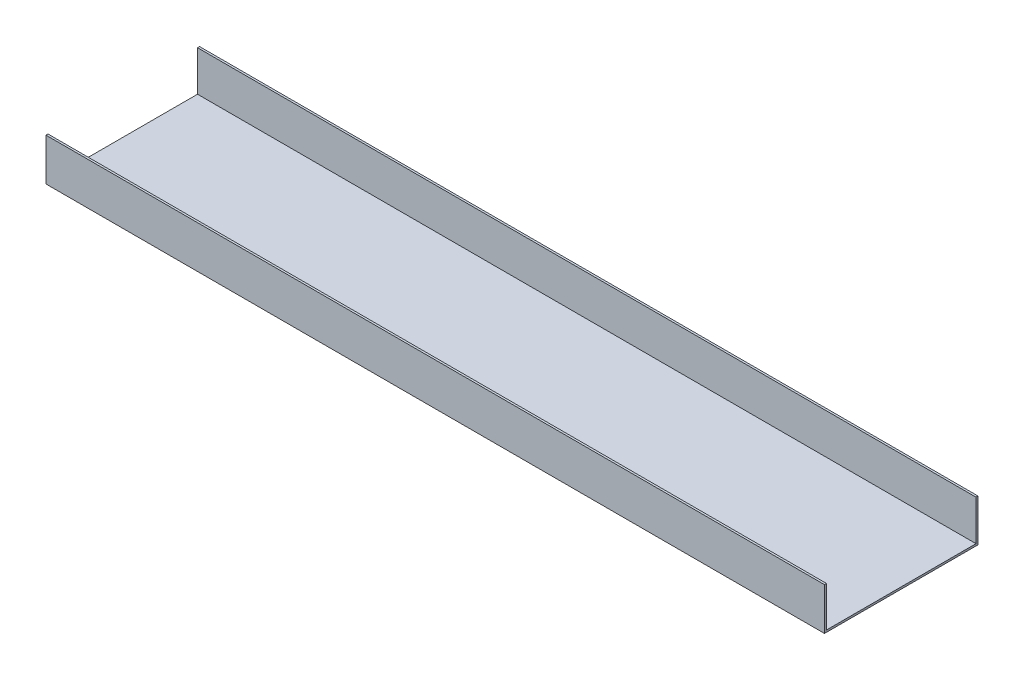
SolidWorks part; units mm, degrees
ref_plane "Front Plane" through (0, 0, 0) normal (0, 0, 1) x (1, 0, 0)
ref_plane "Top Plane" through (0, 0, 0) normal (0, 1, 0) x (1, 0, 0)
ref_plane "Right Plane" through (0, 0, 0) normal (1, 0, 0) x (0, 0, -1)
sketch "Sketch1" plane through (0, 0, 0) normal (0, 1, 0) x (1, 0, 0)
  line L1 (-193.2, 38.1) -> (193.2, 38.1)
  line L2 (-193.2, 38.1) -> (-193.2, -38.1)
  line L3 (-193.2, -38.1) -> (193.2, -38.1)
  line L4 (193.2, 38.1) -> (193.2, -38.1)
  line L5 (-193.2, 38.1) -> (193.2, -38.1) construction
  line L6 (-193.2, -38.1) -> (193.2, 38.1) construction
  point P0 (0, 0)
  dimension "D1" = 386.4
  dimension "D2" = 76.2
extrude "Boss-Extrude1" add sketch "Sketch1" along normal blind 1
sketch "Sketch2" plane through (0, 1, 0) normal (0, 1, 0) x (1, 0, 0)
  line L0 (-193.2, -37.1) -> (193.2, -37.1)
  line L1 (-193.2, 38.1) -> (-193.2, -38.1) construction
  line L2 (193.2, -38.1) -> (193.2, 38.1) construction
  line L3 (-193.2, 37.1) -> (193.2, 37.1)
  line L4 (-193.2, -38.1) -> (193.2, -38.1) construction
  line L5 (193.2, 38.1) -> (-193.2, 38.1) construction
  dimension "D1" = 1
  dimension "D2" = 1
extrude "Extrude-Thin1" add sketch "Sketch2" along normal blind 20 thin contours L0
sketch "Sketch5" plane through (0, 1, 0) normal (0, 1, 0) x (1, 0, 0)
  line L0 (-193.2, 37.1) -> (193.2, 37.1)
  line L1 (-193.2, 38.1) -> (-193.2, -37.1) construction
  line L2 (193.2, -37.1) -> (193.2, 38.1) construction
  line L3 (193.2, 38.1) -> (-193.2, 38.1) construction
  dimension "D1" = 1
extrude "Extrude-Thin2" add sketch "Sketch5" along normal blind 20 thin thin type one direction reverse wall 1
